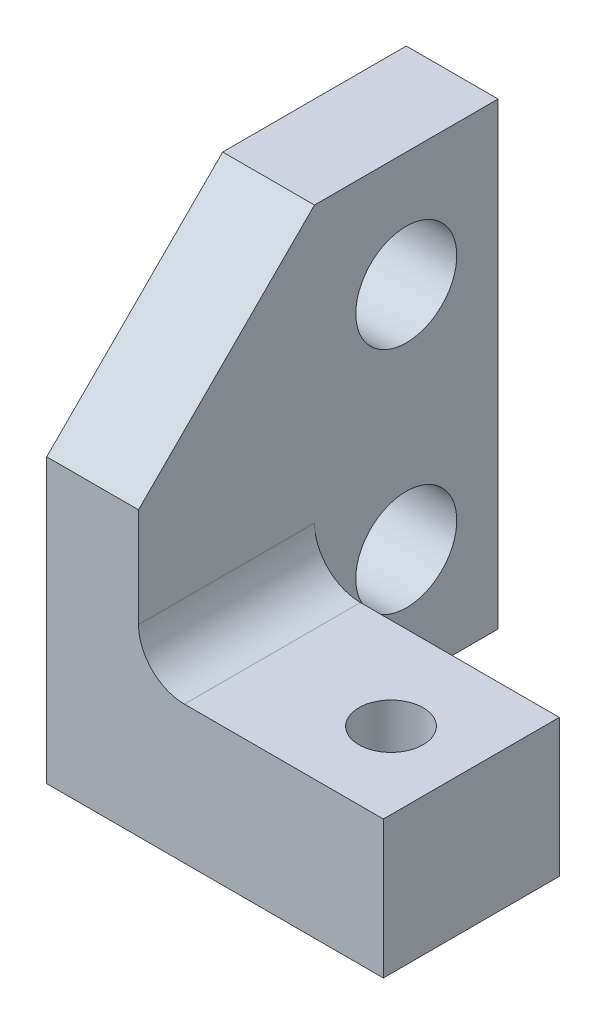
SolidWorks part; units mm, degrees
material "45#"
ref_plane "前视" through (0, 0, 0) normal (0, 0, 1) x (1, 0, 0)
ref_plane "上视" through (0, 0, 0) normal (0, 1, 0) x (1, 0, 0)
ref_plane "右视" through (0, 0, 0) normal (1, 0, 0) x (0, 0, -1)
sketch "草图1" plane through (0, 0, 0) normal (0, 0, 1) x (1, 0, 0)
  line L1 (-11, -15) -> (11, -15)
  line L2 (-11, -15) -> (-11, 15)
  line L3 (-11, 15) -> (11, 15)
  line L4 (11, -15) -> (11, 15)
  line L5 (-11, -15) -> (11, 15) construction
  line L6 (-11, 15) -> (11, -15) construction
  point P0 (0, 0)
  dimension "D1" = 22
  dimension "D2" = 30
extrude "凸台-拉伸1" add sketch "草图1" along normal blind 23.5
sketch "草图2" plane through (0, 15, 0) normal (0, 1, 0) x (1, 0, 0)
  line L1 (11, 0) -> (-5, 0)
  line L2 (11, 0) -> (11, -12)
  line L3 (11, -12) -> (-5, -12)
  line L4 (-5, 0) -> (-5, -12)
  line L5 (-11, -23.5) -> (-11, 0) construction
  dimension "D1" = 6
  dimension "D2" = 12
extrude "切除-拉伸1" cut sketch "草图2" against normal through all
sketch "草图3" plane through (0, 0, 23.5) normal (0, 0, 1) x (1, 0, 0)
  line L1 (11, -6) -> (-5, -6)
  line L2 (11, -6) -> (11, 15)
  line L3 (11, 15) -> (-5, 15)
  line L4 (-5, -6) -> (-5, 15)
  line L5 (11, 15) -> (-11, 15) construction
  line L6 (-11, -15) -> (11, -15) construction
  line L7 (-5, -15) -> (-5, 15) construction
  dimension "D1" = 9
extrude "切除-拉伸2" cut sketch "草图3" against normal through all
hole_wizard "M6 间隙孔1" positions "草图5" profile "草图4" hole size "M6" standard "Gb" end condition through all
sketch "草图5" plane through (-11, 0, 0) normal (-1, 0, 0) x (0, 0, 1)
  line L0 (23.5, 0) -> (11.5883, 0) construction
  line L1 (23.5, 15) -> (23.5, -15) construction
  line L2 (0, 15) -> (0, -15) construction
  point P0 (6, 7.5)
  point P10 (6, -7.5)
  dimension "D1" = 15
  dimension "D2" = 6
sketch "草图4" plane through (-11, 7.5, 6) normal (0, 1, 0) x (0, 0, 1)
  line L0 (0, 0) -> (0, 22)
  line L1 (0, 22) -> (3.3, 22)
  line L2 (3.3, 22) -> (3.3, 0)
  line L5 (3.3, 0) -> (0, 0)
  line L11 (0, -6.35) -> (0, 107.95) construction
  dimension "通孔孔直径" = 6.6
  dimension "通孔孔深度" = 22
hole_wizard "M5 螺纹孔1" positions "草图7" profile "草图6" tap size "M5" standard "Gb" end condition through all
sketch "草图7" plane through (-30.5, -15, 32.5) normal (0, -1, 0) x (-1, 0, 0)
  line L2 (-25.5, 32.5) -> (-25.5, 20.5) construction
  line L3 (-25.5, 20.5) -> (-41.5, 20.5) construction
  point P0 (-36.5, 14.5)
  dimension "D1" = 11
  dimension "D2" = 6
sketch "草图6" plane through (6, -15, 18) normal (1, 0, 0) x (0, 0, -1)
  line L0 (0, 0) -> (0, 30)
  line L1 (0, 30) -> (2.1, 30)
  line L2 (2.1, 30) -> (2.1, 0)
  line L5 (2.1, 0) -> (0, 0)
  line L11 (0, -6.35) -> (0, 107.95) construction
  dimension "通孔螺纹孔钻头直径" = 4.2
  dimension "通孔螺纹孔钻头深度" = 30
cosmetic thread "孔螺蚊线2" parameters "D1"=10, "D2"=5
sketch "草图8" plane through (-11, 0, 0) normal (-1, 0, 0) x (0, 0, 1)
  line L0 (12, 15) -> (23.5, 3.5)
  line L1 (23.5, 15) -> (0, 15) construction
  line L2 (23.5, 15) -> (23.5, -15) construction
  line L3 (23.5, 3.5) -> (23.5, 15)
  line L4 (23.5, 15) -> (12, 15)
  line L5 (0, 15) -> (0, -15) construction
  dimension "D1" = 12
extrude "切除-拉伸3" cut sketch "草图8" against normal through all
fillet "圆角1" radius 3 1 edges at (-5, -6, 17.75)
